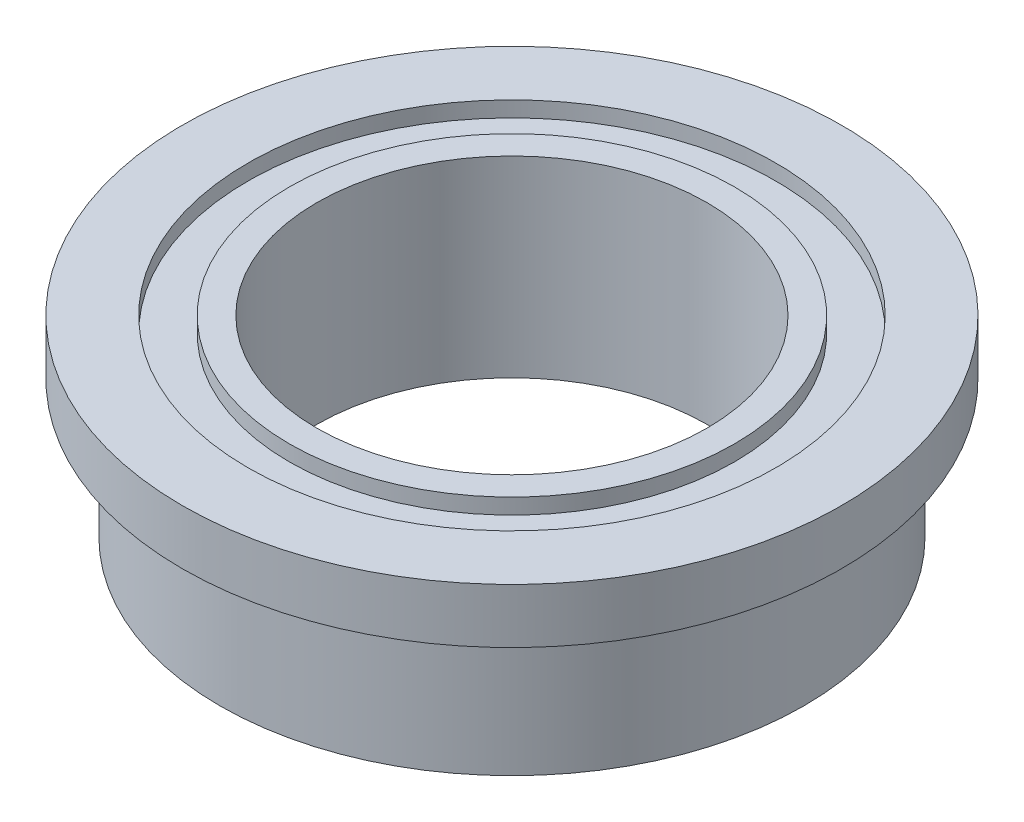
SolidWorks part; units mm, degrees
ref_plane "Front Plane" through (0, 0, 0) normal (0, 0, 1) x (1, 0, 0)
ref_plane "Top Plane" through (0, 0, 0) normal (0, 1, 0) x (1, 0, 0)
ref_plane "Right Plane" through (0, 0, 0) normal (1, 0, 0) x (0, 0, -1)
ref_plane "Plane1" through (0, 0, 0) normal (0, 0, -1) x (-1, 0, 0)
sketch "Sketch1" plane through (0, 0, 0) normal (0, 0, -1) x (-1, 0, 0)
  line L0 (-3.175, 3.1242) -> (-3.6195, 3.1242)
  line L1 (-3.6195, 3.1242) -> (-3.6195, 2.8702)
  line L2 (-3.6195, 2.8702) -> (-4.2926, 2.8702)
  line L3 (-4.2926, 2.8702) -> (-4.2926, 3.1242)
  line L4 (-4.2926, 3.1242) -> (-5.3594, 3.1242)
  line L5 (-5.3594, 3.1242) -> (-5.3594, 2.2352)
  line L6 (-5.3594, 2.2352) -> (-4.7498, 2.2352)
  line L7 (-4.7498, 2.2352) -> (-4.7498, 0)
  line L8 (-4.7498, 0) -> (-4.2926, 0)
  line L9 (-4.2926, 0) -> (-4.2926, 0.254)
  line L10 (-4.2926, 0.254) -> (-3.6195, 0.254)
  line L11 (-3.6195, 0.254) -> (-3.6195, 0)
  line L12 (-3.6195, 0) -> (-3.175, 0)
  line L13 (-3.175, 0) -> (-3.175, 3.1242)
  line L14 (0, 0) -> (0, 3.1242) construction
revolve "Revolve1" add sketch "Sketch1" angle 360 about L14
